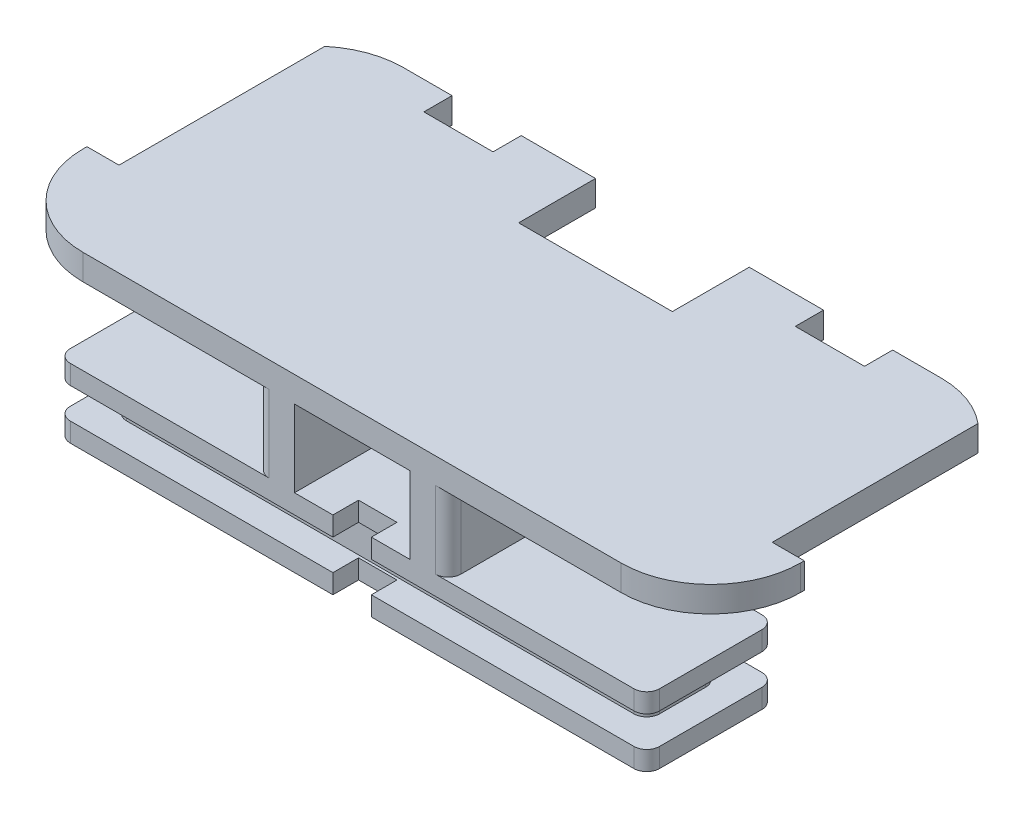
SolidWorks part; units mm, degrees
ref_plane "Front Plane" through (0, 0, 0) normal (0, 0, 1) x (1, 0, 0)
ref_plane "Top Plane" through (0, 0, 0) normal (0, 1, 0) x (1, 0, 0)
ref_plane "Right Plane" through (0, 0, 0) normal (1, 0, 0) x (0, 0, -1)
sketch "Sketch1" plane through (0, 0, 0) normal (0, 1, 0) x (1, 0, 0)
  line L0 (0, -1.5865) -> (0, -28.9135) construction
  line L1 (23, -25.25) -> (-23, -25.25)
  line L2 (23, -25.25) -> (23, -15.25)
  line L3 (23, -15.25) -> (-23, -15.25)
  line L4 (-23, -25.25) -> (-23, -15.25)
  line L5 (-26.4896, -20.25) -> (-19.5104, -20.25) construction
  point P4 (0, -15.25)
  point P5 (-23, -20.25)
  dimension "D1" = 46
  dimension "D2" = 10
extrude "Boss-Extrude1" add sketch "Sketch1" along normal blind 1.5 separate body
fillet "Fillet6" radius 1 4 edges at (-23, 0.75, 25.25) (-23, 0.75, 15.25) (23, 0.75, 15.25) (23, 0.75, 25.25)
ref_plane "Plane5" through (0, -1.2, 0) normal (0, 1, 0) x (1, 0, 0)
mirror "Mirror2" about plane through (0, -1.2, 0) normal (0, 1, 0) of bodies 102
sketch "Sketch2" plane through (0, 0, 0) normal (0, 1, 0) x (1, 0, 0)
  line L0 (20.8, -17.45) -> (-20.8, -17.45)
  line L1 (23, -15.25) -> (-23, -15.25) construction
  line L2 (23, -15.25) -> (23, -25.25) construction
  line L3 (23, -25.25) -> (-23, -25.25) construction
  line L4 (-23, -15.25) -> (-23, -25.25) construction
  line L5 (-20.8, -17.45) -> (-20.8, -23.05)
  line L6 (20.8, -23.05) -> (-20.8, -23.05)
  line L7 (20.8, -17.45) -> (20.8, -23.05)
  line L8 (0, 0) -> (0, -31.754) construction
  point P11 (0, -25.25)
  dimension "D1" = 2.2
extrude "Boss-Extrude2" add sketch "Sketch2" against normal up to next
sketch "Sketch8" plane through (0, 1.5, 0) normal (0, 1, 0) x (1, 0, 0)
  line L1 (4.5, -15.25) -> (7.5, -15.25)
  line L2 (4.5, -15.25) -> (4.5, -25.25)
  line L3 (4.5, -25.25) -> (7.5, -25.25)
  line L4 (7.5, -15.25) -> (7.5, -25.25)
  line L6 (-22, -25.25) -> (22, -25.25) construction
  line L7 (0, -13.8063) -> (0, -29.6789) construction
  dimension "D1" = 3
  dimension "D2" = 4.5
extrude "Boss-Extrude7" add sketch "Sketch8" along normal blind 6
mirror "Mirror4" about plane through (0, 0, 0) normal (1, 0, 0) of bodies 115 109 106
fillet "Fillet1" radius 1 4 edges at (-20.8, -1.2, 23.05) (-20.8, -1.2, 17.45) (20.8, -1.2, 23.05) (20.8, -1.2, 17.45)
fillet "Fillet4" radius 1 4 edges at (-7.5, 4.5, 15.25) (-7.5, 4.5, 25.25) (7.5, 4.5, 15.25) (7.5, 4.5, 25.25)
sketch "Sketch4" plane through (0, 7.5, 0) normal (0, 1, 0) x (1, 0, 0)
  line L0 (0, -2.3682) -> (0, -36.2987) construction
  line L1 (-23, -20.25) -> (32.1904, -20.25) construction
  line L2 (-23, -16.25) -> (-23, -24.25) construction
  line L3 (-22, -25.25) -> (-6.5, -25.25) construction
  line L4 (-28, -0.25) -> (28, -0.25)
  line L5 (-28, -0.25) -> (-28, -25.25)
  line L6 (-28, -25.25) -> (28, -25.25)
  line L7 (28, -0.25) -> (28, -25.25)
  dimension "D1" = 56
  dimension "D2" = 25
extrude "Boss-Extrude5" add sketch "Sketch4" along normal blind 2
fillet "Fillet7" radius 7 4 edges at (28, 8.5, 25.25) (-28, 8.5, 25.25) (28, 8.5, 0.25) (-28, 8.5, 0.25)
sketch "Sketch5" plane through (0, 9.5, 0) normal (0, 1, 0) x (1, 0, 0)
  line L9 (28, -17.55) -> (25.2, -17.55)
  line L10 (25.2, -17.55) -> (25.2, -7.95)
  line L11 (28, -7.95) -> (25.2, -7.95)
  line L12 (28, -17.55) -> (28, -7.95)
  line L13 (0, -39.7353) -> (0, -2.3026) construction
  line L14 (-28, -17.55) -> (-28, -7.95)
  line L15 (-28, -7.95) -> (-25.2, -7.95)
  line L16 (-25.2, -17.55) -> (-25.2, -7.95)
  line L17 (-28, -17.55) -> (-25.2, -17.55)
  line L18 (-29.4279, -12.75) -> (29.9154, -12.75) construction
  dimension "D1" = 9.6
  dimension "D2" = 2.8
extrude "Boss-Extrude6" [suppressed] add sketch "Sketch5" along normal blind 15.6
sketch "Sketch6" plane through (0, 9.5, 0) normal (0, 1, 0) x (1, 0, 0)
  line L1 (6, -0.25) -> (-6, -0.25)
  line L2 (6, -0.25) -> (6, -6.25)
  line L3 (6, -6.25) -> (-6, -6.25)
  line L4 (-6, -0.25) -> (-6, -6.25)
  line L5 (6, -0.25) -> (-6, -6.25) construction
  line L6 (6, -6.25) -> (-6, -0.25) construction
  line L9 (21, -0.25) -> (-21, -0.25) construction
  point P0 (0, -11.67)
  dimension "D1" = 6
  dimension "D2" = 12
extrude "Cut-Extrude1" cut sketch "Sketch6" against normal through all
sketch "Sketch9" plane through (0, 9.5, 0) normal (0, 1, 0) x (1, 0, 0)
  line L0 (0, -29.637) -> (0, 5.7748) construction
  line L1 (-28, -17.95) -> (-28, 7.05)
  line L2 (25.5, -17.95) -> (28, -17.95)
  line L3 (25.5, -17.95) -> (25.5, 7.05)
  line L4 (25.5, 7.05) -> (28, 7.05)
  line L5 (28, -17.95) -> (28, 7.05)
  line L6 (-25.5, 7.05) -> (-28, 7.05)
  line L7 (-25.5, -17.95) -> (-25.5, 7.05)
  line L8 (-25.5, -17.95) -> (-28, -17.95)
  line L9 (28, -17.75) -> (25.5, -17.75) construction
  dimension "D1" = 2.5
  dimension "D2" = 0.2
extrude "Cut-Extrude2" cut sketch "Sketch9" against normal up to next
sketch "Sketch10" plane through (0, 9.5, 0) normal (0, 1, 0) x (1, 0, 0)
  line L0 (17.2, -0.25) -> (11.8, -0.25)
  line L1 (21, -0.25) -> (6, -0.25) construction
  line L2 (11.8, -0.25) -> (11.8, -2.45)
  line L3 (11.8, -2.45) -> (17.2, -2.45)
  line L4 (17.2, -2.45) -> (17.2, -0.25)
  line L5 (0, 4.3832) -> (0, -27.4685) construction
  line L6 (12, -2.25) -> (12, -0.25) construction
  line L7 (17, -0.25) -> (17, -2.25) construction
  line L8 (-19, -2.25) -> (19, -2.25) construction
  line L9 (-17.2, -2.45) -> (-17.2, -0.25)
  line L10 (-11.8, -2.45) -> (-17.2, -2.45)
  line L11 (-11.8, -0.25) -> (-11.8, -2.45)
  line L12 (-17.2, -0.25) -> (-11.8, -0.25)
  dimension "D1" = 0.2
  dimension "D2" = 0.2
  dimension "D3" = 0.2
extrude "Cut-Extrude3" cut sketch "Sketch10" against normal up to next
sketch "Эскиз1" plane through (0, 1.5, 0) normal (0, -1, 0) x (1, 0, 0)
  line L0 (0, 0) -> (0, 29.1656) construction
  line L1 (-1.5, 25.25) -> (1.5, 25.25)
  line L2 (-22, 25.25) -> (22, 25.25) construction
  line L3 (1.5, 25.25) -> (1.5, 23.25)
  line L4 (1.5, 23.25) -> (-1.5, 23.25)
  line L5 (-1.5, 25.25) -> (-1.5, 23.25)
  point P10 (0, 23.25)
  point P11 (0, 25.25)
  dimension "D1" = 2
  dimension "D2" = 3
extrude "Вырез-Вытянуть1" cut sketch "Эскиз1" along normal through all
